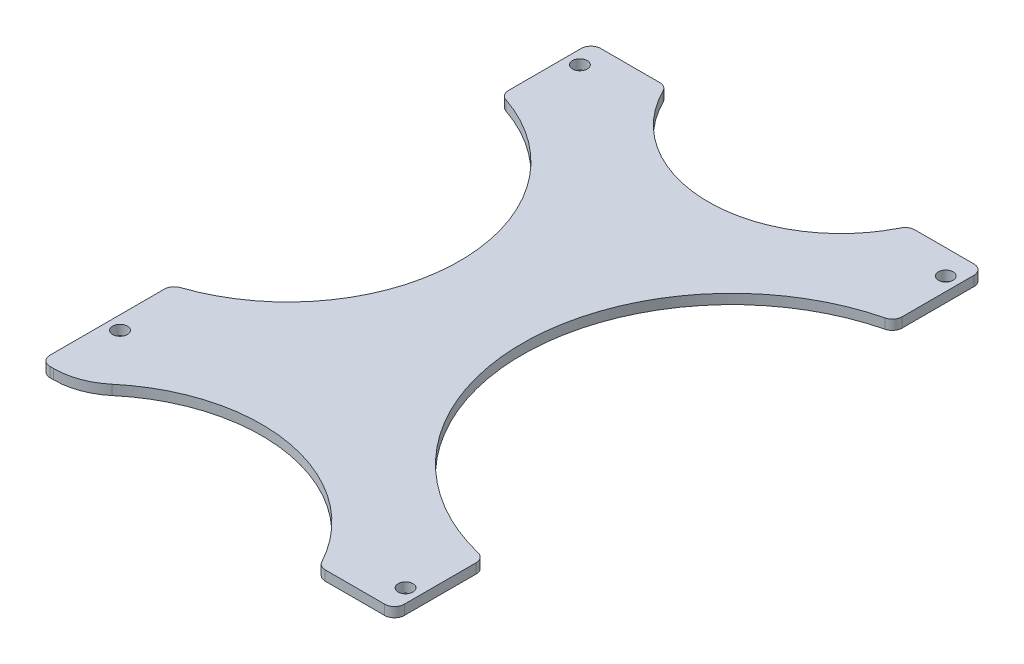
SolidWorks part; units mm, degrees
ref_plane "Front Plane" through (0, 0, 0) normal (0, 0, 1) x (1, 0, 0)
ref_plane "Top Plane" through (0, 0, 0) normal (0, 1, 0) x (1, 0, 0)
ref_plane "Right Plane" through (0, 0, 0) normal (1, 0, 0) x (0, 0, -1)
sketch "Sketch1" plane through (0, 0, 0) normal (0, 1, 0) x (1, 0, 0)
  line L1 (0, 0) -> (80, 0)
  line L2 (0, 0) -> (0, 120)
  line L3 (0, 120) -> (80, 120)
  line L4 (80, 0) -> (80, 120)
  dimension "D1" = 80
  dimension "D2" = 120
extrude "Boss-Extrude1" add sketch "Sketch1" along normal blind 2
sketch "Sketch2" plane through (0, 2, 0) normal (0, 1, 0) x (1, 0, 0)
  line L0 (80, 120) -> (0, 120) construction
  line L1 (0, 120) -> (0, 0) construction
  line L2 (40, 120) -> (40, 49.6412) construction
  line L3 (0, 60) -> (80, 60) construction
  line L4 (80, 0) -> (80, 120) construction
  circle A0 centre (2.75, 115) radius 1.5
  circle A1 centre (77.25, 115) radius 1.5
  circle A2 centre (77.25, 5) radius 1.5
  circle A3 centre (2.75, 21.35) radius 1.5
  point P18 (0, 0)
  point P19 (0, 0)
  point P20 (0, 0)
  dimension "D1" = 3
  dimension "D4" = 93.65
  dimension "D2" = 5
  dimension "D3" = 2.75
extrude "Cut-Extrude1" cut sketch "Sketch2" against normal through all
sketch "Sketch3" plane through (0, 2, 0) normal (0, 1, 0) x (1, 0, 0)
  line L0 (80, 0) -> (80, 120) construction
  line L1 (2.75, 128.5) -> (77.25, 128.5)
  line L2 (-10.75, 115) -> (-10.75, 21.35)
  line L3 (-10.75, 7.85) -> (-10.75, -8.5)
  line L4 (77.25, -8.5) -> (-10.75, -8.5)
  line L5 (90.75, 5) -> (90.75, 115)
  line L6 (2.75, 7.85) -> (-10.75, 7.85)
  arc A0 (15.1667, 120.2987) -> (2.75, 128.5) centre (2.75, 115) ccw
  arc A1 (80, 101.7831) -> (90.75, 115) centre (77.25, 115) ccw
  arc A2 (-0.7672, 34.3838) -> (-10.75, 21.35) centre (2.75, 21.35) ccw
  arc A3 (65.0161, -0.7081) -> (77.25, -8.5) centre (77.25, 5) ccw
  arc A4 (15.1667, 120.2987) -> (64.8333, 120.2987) centre (40, 130.8961) ccw
  arc A5 (-0.7672, 101.9662) -> (-0.7672, 34.3838) centre (-9.886, 68.175) cw
  arc A6 (11.4693, 11.0435) -> (65.0161, -0.7081) centre (33.7518, -15.2955) cw
  arc A7 (80, 18.2169) -> (80, 101.7831) centre (88.6936, 60) cw
  arc A8 (90.75, 5) -> (80, 18.2169) centre (77.25, 5) ccw
  arc A9 (77.25, 128.5) -> (64.8333, 120.2987) centre (77.25, 115) ccw
  arc A10 (-10.75, 115) -> (-0.7672, 101.9662) centre (2.75, 115) ccw
  arc A11 (2.75, 7.85) -> (11.4693, 11.0435) centre (2.75, 21.35) ccw
  dimension "D1" = 27
  dimension "D2" = 35
  dimension "D3" = 34.5
  dimension "D4" = 27
extrude "Cut-Extrude2" cut sketch "Sketch3" against normal through all
fillet "Fillet1" radius 2 11 edges at (0, 1, -34.6002) (0, 1, -101.7498) (15.2963, 1, -120) (64.7037, 1, -120) (80, 1, -18.2169) (80, 1, -101.7831) (64.6759, 1, 0) (0, 1, -7.85) (80, 1, 0) (80, 1, -120) (0, 1, -120)
